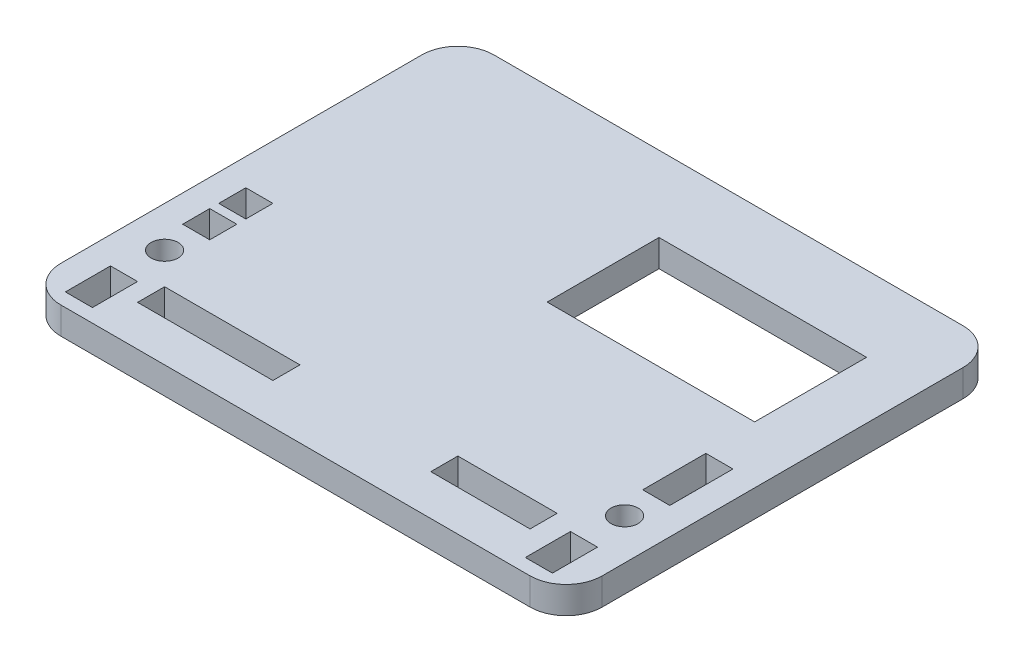
SolidWorks part; units mm, degrees
ref_plane "Alzado" through (0, 0, 0) normal (0, 0, 1) x (1, 0, 0)
ref_plane "Planta" through (0, 0, 0) normal (0, 1, 0) x (1, 0, 0)
ref_plane "Vista lateral" through (0, 0, 0) normal (1, 0, 0) x (0, 0, -1)
sketch "Croquis1" plane through (0, 0, 0) normal (0, 0, 1) x (-1, 0, 0)
  line L0 (41781.9088, 309.1991) -> (41833.9088, 309.1991)
  line L1 (41786.4088, 313.6991) -> (41796.4088, 313.6991)
  line L5 (41780.9273, 315.6956) -> (41783.4299, 315.6956)
  line L17 (41831.9088, 310.6991) -> (41834.4088, 310.6991)
  line L21 (41831.9088, 323.6991) -> (41834.4088, 323.6991)
  line L23 (41831.9088, 326.6991) -> (41834.4088, 326.6991)
  line L25 (41831.9088, 327.6991) -> (41834.4088, 327.6991)
  line L27 (41831.9088, 330.6991) -> (41834.4088, 330.6991)
  line L33 (41837.9088, 313.1991) -> (41837.9088, 353.1991)
  line L34 (41833.9088, 357.1991) -> (41781.9088, 357.1991)
  line L35 (41777.9088, 353.1991) -> (41777.9088, 313.1991)
  line L37 (41786.4088, 316.6991) -> (41796.4088, 316.6991)
  line L46 (41831.9088, 315.6991) -> (41834.4088, 315.6991)
  line L47 (41834.4088, 310.6991) -> (41834.9088, 310.6991)
  line L49 (41831.9088, 310.6991) -> (41831.9088, 315.6991)
  line L50 (41834.9088, 310.6991) -> (41834.9088, 315.6991)
  line L51 (41834.4088, 330.6991) -> (41834.9088, 330.6991)
  line L52 (41834.4088, 327.6991) -> (41834.9088, 327.6991)
  line L53 (41834.4088, 326.6991) -> (41834.9088, 326.6991)
  line L54 (41834.4088, 323.6991) -> (41834.9088, 323.6991)
  line L55 (41831.9088, 327.6991) -> (41831.9088, 330.6991)
  line L56 (41834.9088, 327.6991) -> (41834.9088, 330.6991)
  line L57 (41834.9088, 323.6991) -> (41834.9088, 326.6991)
  line L58 (41831.9088, 323.6991) -> (41831.9088, 326.6991)
  line L59 (41834.4088, 315.6991) -> (41834.9088, 315.6991)
  line L61 (41780.9299, 310.6991) -> (41780.9273, 315.6956)
  line L63 (41780.9299, 310.6991) -> (41783.9299, 310.6991)
  line L64 (41783.9299, 310.6991) -> (41783.9272, 315.6956)
  line L69 (41783.4299, 315.6956) -> (41783.9272, 315.6956)
  line L78 (41786.4088, 313.6991) -> (41786.4088, 316.6991)
  line L79 (41796.4088, 313.6991) -> (41797.4088, 313.6991)
  line L80 (41797.4088, 313.6991) -> (41797.4088, 316.6991)
  line L81 (41797.4088, 316.6991) -> (41796.4088, 316.6991)
  line L83 (41814.9088, 313.6991) -> (41814.9088, 316.6991)
  line L89 (41829.9088, 316.6991) -> (41829.9088, 313.6991)
  line L90 (41814.9088, 316.6991) -> (41829.9088, 316.6991)
  line L91 (41814.9088, 316.6991) -> (41814.9088, 313.6991)
  line L93 (41783.9231, 323.6991) -> (41780.9194, 323.6991)
  line L94 (41783.9231, 323.6991) -> (41783.9231, 330.6991)
  line L95 (41783.9231, 330.6991) -> (41780.9194, 330.6991)
  line L96 (41780.9194, 323.6991) -> (41780.9194, 330.6991)
  line L98 (41814.9088, 313.6991) -> (41829.9088, 313.6991)
  line L123 (41784.2382, 348.822) -> (41807.2382, 348.822)
  line L124 (41784.2382, 348.822) -> (41784.2382, 336.422)
  line L125 (41784.2382, 336.422) -> (41807.2382, 336.422)
  line L126 (41807.2382, 348.822) -> (41807.2382, 336.422)
  arc A0 (41777.9088, 313.1991) -> (41781.9088, 309.1991) centre (41781.9088, 313.1991) ccw
  circle A2 centre (41833.4088, 320.1991) radius 1.5
  arc A3 (41781.9088, 357.1991) -> (41777.9088, 353.1991) centre (41781.9088, 353.1991) ccw
  arc A4 (41837.9088, 353.1991) -> (41833.9088, 357.1991) centre (41833.9088, 353.1991) ccw
  arc A5 (41833.9088, 309.1991) -> (41837.9088, 313.1991) centre (41833.9088, 313.1991) ccw
  circle A7 centre (41782.4299, 320.1977) radius 1.5
extrude "Saliente-Extruir1" add sketch "Croquis1" along normal blind 3
move or copy body "Sólido-Mover/Copiar2" bodies to move or copy 101 copy no rotation origin (0, -333.1991, 1.5) rotation axis (1, 0, 0) rotation angle 90
